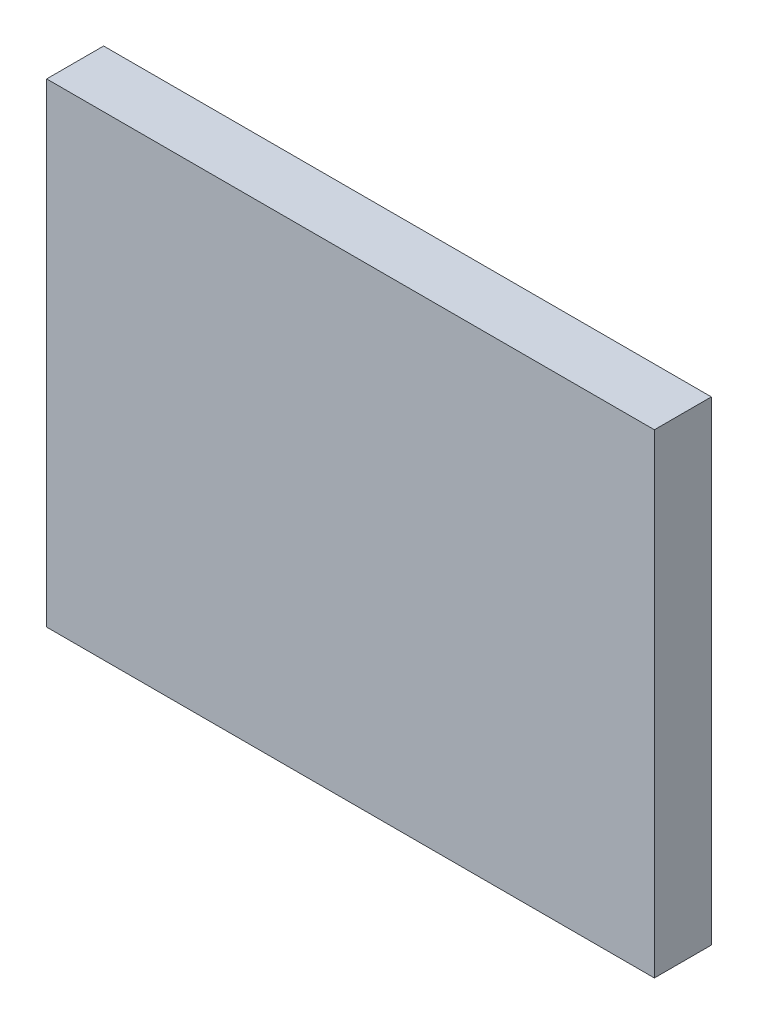
SolidWorks part; units mm, degrees
ref_plane "Front" through (0, 0, 0) normal (0, 0, 1) x (1, 0, 0)
ref_plane "Top" through (0, 0, 0) normal (0, 1, 0) x (1, 0, 0)
ref_plane "Right" through (0, 0, 0) normal (1, 0, 0) x (0, 0, -1)
sketch "Sketch1" plane through (0, 0, 0) normal (0, 0, 1) x (1, 0, 0)
  line L1 (101.6, 0) -> (-101.6, 0)
  line L2 (101.6, 0) -> (101.6, -158.75)
  line L3 (101.6, -158.75) -> (-101.6, -158.75)
  line L4 (-101.6, 0) -> (-101.6, -158.75)
extrude "Boss-Extrude1" add sketch "Sketch1" along normal blind 19.05
